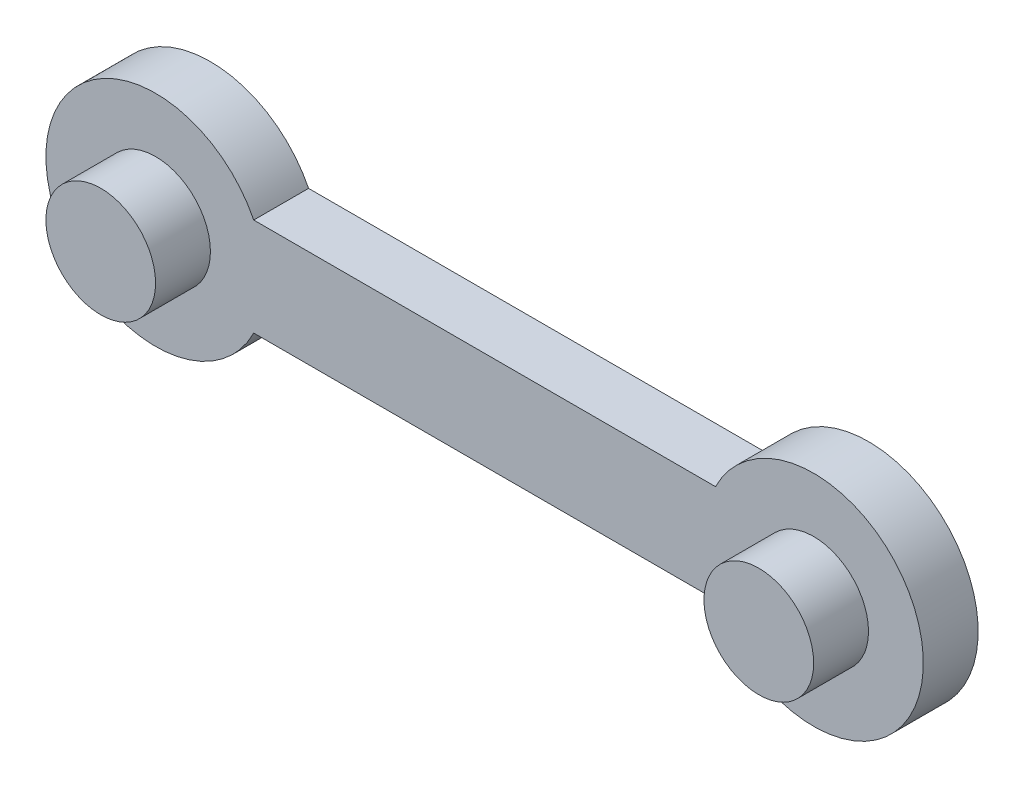
SolidWorks part; units mm, degrees
ref_plane "前视基准面" through (0, 0, 0) normal (0, 0, 1) x (1, 0, 0)
ref_plane "上视基准面" through (0, 0, 0) normal (0, 1, 0) x (1, 0, 0)
ref_plane "右视基准面" through (0, 0, 0) normal (1, 0, 0) x (0, 0, -1)
other "Configuration Table"
sketch "草图1" plane through (0, 0, 0) normal (0, 0, 1) x (1, 0, 0)
  line L0 (8.9501, 4.4605) -> (51.0499, 4.4605)
  line L2 (8.9501, -4.4605) -> (51.0499, -4.4605)
  circle A4 centre (0, 0) radius 10
  circle A5 centre (60, 0) radius 10
  dimension "D2" = 20
  dimension "D3" = 20
  dimension "D1" = 60
extrude "凸台-拉伸3" add sketch "草图1" along normal blind 5 contours A4 | A5 L0 A4 L2 | A5
sketch "草图3" plane through (0, 0, 5) normal (0, 0, 1) x (1, 0, 0)
  circle A1 centre (60, 0) radius 5
extrude "凸台-拉伸4" add sketch "草图3" along normal blind 5
sketch "草图4" plane through (0, 0, 5) normal (0, 0, 1) x (1, 0, 0)
  circle A0 centre (0, 0) radius 5
  dimension "D1" = 10
extrude "凸台-拉伸5" add sketch "草图4" along normal blind 5
